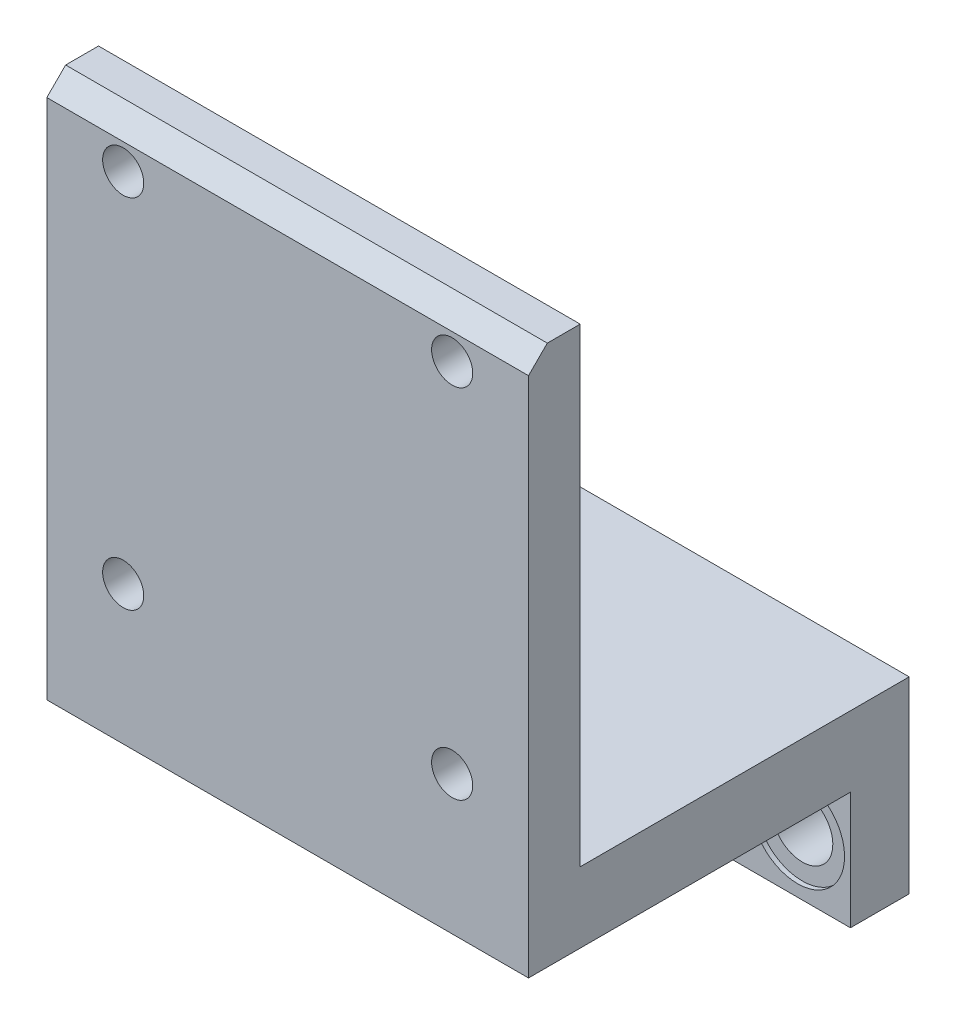
SolidWorks part; units mm, degrees
ref_plane "前视基准面" through (0, 0, 0) normal (0, 0, 1) x (1, 0, 0)
ref_plane "上视基准面" through (0, 0, 0) normal (0, 1, 0) x (1, 0, 0)
ref_plane "右视基准面" through (0, 0, 0) normal (1, 0, 0) x (0, 0, -1)
sketch "草图1" plane through (0, 0, 0) normal (1, 0, 0) x (0, 0, -1)
  line L0 (0, 0) -> (137, 0)
  line L1 (137, 0) -> (137, -50)
  line L2 (137, -50) -> (162, -50)
  line L3 (162, -50) -> (162, 30)
  line L4 (162, 30) -> (22, 30)
  line L5 (22, 30) -> (22, 230)
  line L6 (22, 230) -> (0, 230)
  line L7 (0, 230) -> (0, 0)
  point P7 (137, -25)
  dimension "D1" = 162
  dimension "D2" = 140
  dimension "D3" = 280
  dimension "D4" = 200
  dimension "D5" = 30
  dimension "D6" = 25
extrude "凸台-拉伸1" add sketch "草图1" along normal blind 205
hole_wizard "M20 螺纹孔1" positions "3D草图1" profile "草图2" tap size "M20" standard "GB" end condition up to next
sketch3d "3D草图1"
  line L0 (0, 230, 0) -> (0, 0, 0) construction
  line L1 (205, 230, 0) -> (0, 230, 0) construction
  point P0 (32.5, 211, 0)
  dimension "D1" = 32.5
  dimension "D2" = 19
sketch "草图2" plane through (32.5, 211, 0) normal (1, 0, 0) x (0, -1, 0)
  line L0 (0, 0) -> (0, 22.001)
  line L1 (0, 22.001) -> (8.75, 22.001)
  line L2 (8.75, 22.001) -> (8.75, 0)
  line L5 (8.75, 0) -> (0, 0)
  line L11 (0, -6.35) -> (0, 107.95) construction
  dimension "通孔螺纹孔钻头直径" = 17.5
  dimension "通孔螺纹孔钻头深度" = 22.001
cosmetic thread "孔螺蚊线1" parameters "D2"=20
pattern_linear "阵列(线性)1" count 2 spacing 140 along (1, 0, 0) count 2 spacing 152 along (0, -1, 0) of "M20 螺纹孔1"
hole_wizard "M20 六角头螺栓的柱形沉头孔1" positions "3D草图2" profile "草图3" counterbore size "M20" standard "GB" end condition up to next
sketch3d "3D草图2"
  line L0 (205, -50, -137) -> (0, -50, -137) construction
  line L1 (0, 0, -137) -> (0, -50, -137) construction
  point P0 (22.5, -25, -137)
  dimension "D1" = 25
  dimension "D2" = 22.5
sketch "草图3" plane through (22.5, -25, -137) normal (1, 0, 0) x (0, -1, 0)
  line L0 (0, 0) -> (0, 25.001)
  line L1 (0, 25.001) -> (13, 25.001)
  line L3 (13, 25.001) -> (13, 2)
  line L4 (13, 2) -> (20, 2)
  line L5 (20, 2) -> (20, 0)
  line L7 (20, 0) -> (0, 0)
  line L11 (0, -6.35) -> (0, 107.95) construction
  dimension "通孔孔直径" = 26
  dimension "通孔孔深度" = 25.001
  dimension "柱形沉头孔直径" = 40
  dimension "柱形沉头孔深度" = 2
pattern_linear "阵列(线性)2" count 3 spacing 80 along (1, 0, 0) of "M20 六角头螺栓的柱形沉头孔1"
chamfer "倒角1" distance 8 angle 45 1 edges at (102.5, 230, 0)
